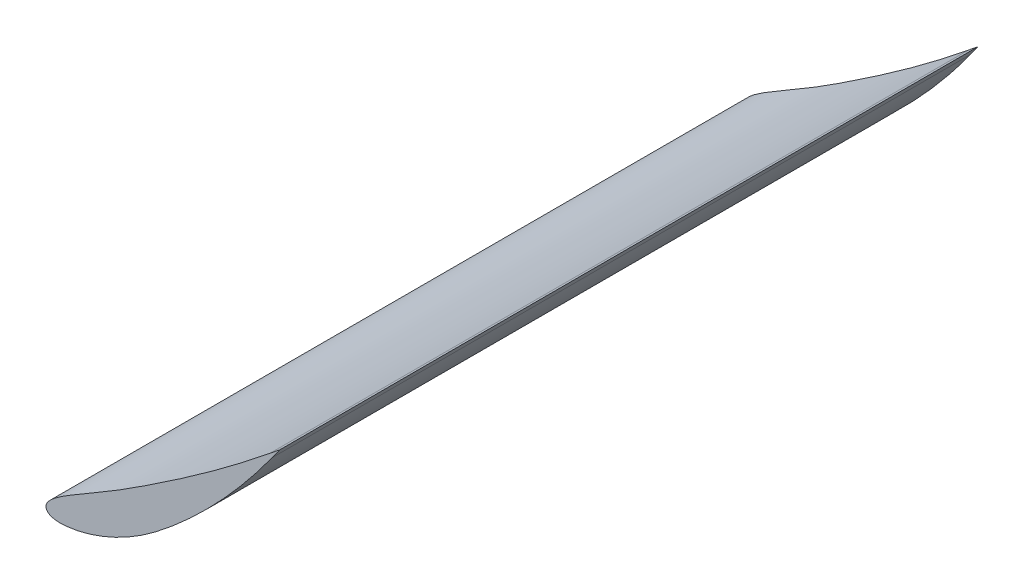
SolidWorks part; units mm, degrees
ref_plane "Front Plane" through (0, 0, 0) normal (0, 0, 1) x (1, 0, 0)
ref_plane "Top Plane" through (0, 0, 0) normal (0, 1, 0) x (1, 0, 0)
ref_plane "Right Plane" through (0, 0, 0) normal (1, 0, 0) x (0, 0, -1)
sketch "Sketch3" plane through (0, 0, 0) normal (0, 0, 1) x (1, 0, 0)
  line L7 (0, 0) -> (143.0551, 0) construction
  line L14 (0, 0) -> (-43.0922, 59.3113) construction
  line L16 (137.7846, 99.6282) -> (143.8432, 104.5082)
  line L17 (143.8432, 104.5082) -> (139.047, 97.8536)
  line L19 (0, 0) -> (143.8432, 104.5082) construction
  spline S1 degree 3 poles (139.047, 97.8536) (137.9791, 96.372) (136.9063, 94.8948) (134.7378, 91.9614) (133.6441, 90.5032) (130.3353, 86.1544) (128.0924, 83.289) (121.253, 74.7943) (116.5469, 69.2652) (106.836, 58.4805) (101.8315, 53.2244) (91.4971, 43.0102) (86.1677, 38.0516) (79.2681, 32.0709) (77.8753, 30.8849) (75.0687, 28.5405) (73.6557, 27.3831) (69.3889, 23.9535) (66.513, 21.715) (60.6088, 17.4706) (57.5865, 15.4556) (51.3909, 11.6561) (48.2175, 9.8719) (43.3309, 7.3886) (41.681, 6.5931) (38.3355, 5.0716) (36.644, 4.3477) (31.5368, 2.3048) (28.0787, 1.1075) (22.7931, -0.3842) (21.0147, -0.8303) (18.3168, -1.4057) (17.4109, -1.5819) (15.5965, -1.8965) (14.6878, -2.0347) (12.8669, -2.2667) (11.9548, -2.3607) (10.1262, -2.4919) (9.2098, -2.53) (7.8306, -2.5276) (7.3701, -2.5169) (6.4472, -2.4709) (5.9835, -2.4352) (5.0628, -2.331) (4.6052, -2.2632) (3.6979, -2.0835) (3.2466, -1.9704) (2.3632, -1.6821) (1.9347, -1.5083) (1.324, -1.1751) (1.1245, -1.0511) (0.7477, -0.7796) (0.5697, -0.6317) (0.2396, -0.3061) (0.0863, -0.1263) (-0.1779, 0.2554) (-0.2903, 0.4577) (-0.474, 0.8861) (-0.5439, 1.1108) (-0.6319, 1.5642) (-0.6501, 1.7967) (-0.638, 2.2647) (-0.6084, 2.4944) (-0.512, 2.9469) (-0.4447, 3.1711) (-0.1978, 3.8251) (0.0238, 4.2298) (0.53, 5.0044) (0.8144, 5.3745) (1.4124, 6.074) (1.7272, 6.4071) (2.702, 7.3743) (3.3935, 7.9754) (4.8173, 9.1344) (5.5522, 9.6908) (7.7815, 11.3093) (9.3069, 12.325) (12.3907, 14.3027) (13.9501, 15.2631) (17.0854, 17.1573) (18.6616, 18.0906) (23.4009, 20.8729) (26.5741, 22.7057) (32.9063, 26.3943) (36.0654, 28.2489) (42.3461, 32.0131) (45.4678, 33.9225) (50.1114, 36.8436) (51.6528, 37.8268) (54.7206, 39.8153) (56.2474, 40.8198) (60.8261, 43.8361) (63.8782, 45.8476) (73.0088, 51.9194) (79.0674, 56.0091) (91.09, 64.327) (97.0543, 68.5549) (108.8737, 77.1707) (114.7293, 81.5578) (123.4332, 88.2551) (126.322, 90.5067) (130.6348, 93.9092) (132.069, 95.0477) (134.9312, 97.3323) (136.3585, 98.4795) (137.7846, 99.6282) knots 0 0 0 0 0.015625 0.015625 0.03125 0.03125 0.0625 0.0625 0.125 0.125 0.1875 0.1875 0.25 0.25 0.265625 0.265625 0.28125 0.28125 0.3125 0.3125 0.34375 0.34375 0.375 0.375 0.390625 0.390625 0.40625 0.40625 0.4375 0.4375 0.453125 0.453125 0.460937 0.460937 0.46875 0.46875 0.476562 0.476562 0.484375 0.484375 0.488281 0.488281 0.492187 0.492187 0.496094 0.496094 0.5 0.5 0.503906 0.503906 0.505859 0.505859 0.507812 0.507812 0.509766 0.509766 0.511719 0.511719 0.513672 0.513672 0.515625 0.515625 0.517578 0.517578 0.519531 0.519531 0.523437 0.523437 0.527344 0.527344 0.53125 0.53125 0.539062 0.539062 0.546875 0.546875 0.5625 0.5625 0.578125 0.578125 0.59375 0.59375 0.625 0.625 0.65625 0.65625 0.6875 0.6875 0.703125 0.703125 0.71875 0.71875 0.75 0.75 0.8125 0.8125 0.875 0.875 0.9375 0.9375 0.96875 0.96875 0.984375 0.984375 1 1 1 1
  dimension "D1" = 126
  dimension "D2" = 177.8
extrude "Boss-Extrude3" add sketch "Sketch3" along normal blind 431.8
sketch "Sketch4" plane through (0, 0, 0) normal (0, 0, -1) x (-1, 0, 0)
  line L0 (0, 0) -> (-143.8432, 104.5082) construction
sketch "Sketch5" plane through (0, 0, 431.8) normal (0, 0, 1) x (1, 0, 0)
  line L0 (0, 0) -> (143.8432, 104.5082) construction
sketch3d "3DSketch1"
  line L0 (0, 0, 0) -> (0, 0, 431.8)
